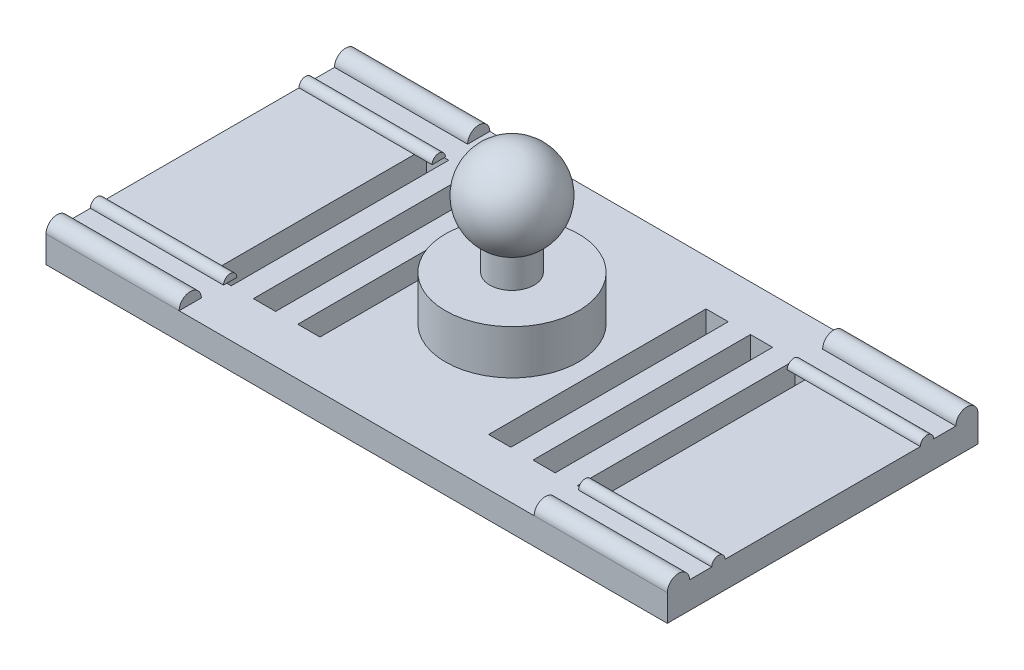
SolidWorks part; units mm, degrees
ref_plane "前视" through (0, 0, 0) normal (0, 0, 1) x (1, 0, 0)
ref_plane "上视" through (0, 0, 0) normal (0, 1, 0) x (1, 0, 0)
ref_plane "右视" through (0, 0, 0) normal (1, 0, 0) x (0, 0, -1)
sketch "草图1" plane through (0, 0, 0) normal (0, 1, 0) x (1, 0, 0)
  line L0 (-66.27, -34.8522) -> (73.73, -34.8522)
  line L2 (-66.27, 35.1478) -> (-66.27, -34.8522)
  line L4 (73.73, 35.1478) -> (73.73, -34.8522)
  line L5 (-66.27, 35.1478) -> (73.73, 35.1478)
extrude "凸台-拉伸1" add sketch "草图1" along normal blind 6
sketch "草图2" plane through (0, 6, 0) normal (0, 1, 0) x (1, 0, 0)
  circle A1 centre (3.73, 0.1478) radius 15
extrude "凸台-拉伸2" add sketch "草图2" along normal blind 10
sketch "草图5" plane through (0, 16, 0) normal (0, 1, 0) x (1, 0, 0)
  circle A0 centre (3.73, 0.1478) radius 5
extrude "凸台-拉伸4" add sketch "草图5" along normal blind 15
sketch "草图6" plane through (0, 31, 0) normal (0, 1, 0) x (1, 0, 0)
  line L0 (3.73, 10.0478) -> (3.73, -9.7522)
  arc A0 (3.73, -9.7522) -> (3.73, 10.0478) centre (3.73, 0.1478) ccw
revolve "旋转2" add sketch "草图6" angle 360 about L0
sketch "草图7" plane through (0, 0, 0) normal (0, -1, 0) x (1, 0, 0)
  line L0 (27.73, -24.8809) -> (22.73, -24.8809)
  line L1 (-35.27, -24.8809) -> (-40.27, -24.8809)
  line L2 (-35.27, -24.8809) -> (-35.27, 24.1191)
  line L3 (27.73, -24.8809) -> (27.73, 24.1191)
  line L4 (37.73, -24.8809) -> (32.73, -24.8809)
  line L5 (37.73, -24.8809) -> (37.73, 24.1191)
  line L6 (37.73, 24.1191) -> (32.73, 24.1191)
  line L7 (32.73, -24.8809) -> (32.73, 24.1191)
  line L8 (27.73, 24.1191) -> (22.73, 24.1191)
  line L9 (22.73, -24.8809) -> (22.73, 24.1191)
  line L10 (-35.27, 24.1191) -> (-40.27, 24.1191)
  line L11 (-40.27, -24.8809) -> (-40.27, 24.1191)
  line L12 (47.73, -24.8809) -> (42.73, -24.8809)
  line L13 (42.73, -24.8809) -> (42.73, 24.1191)
  line L14 (47.73, 24.1191) -> (42.73, 24.1191)
  line L15 (47.73, -24.8809) -> (47.73, 24.1191)
  line L26 (-25.27, -24.8809) -> (-30.27, -24.8809)
  line L27 (-25.27, -24.8809) -> (-25.27, 24.1191)
  line L28 (-15.27, -24.8809) -> (-20.27, -24.8809)
  line L29 (-15.27, -24.8809) -> (-15.27, 24.1191)
  line L30 (-15.27, 24.1191) -> (-20.27, 24.1191)
  line L31 (-20.27, -24.8809) -> (-20.27, 24.1191)
  line L32 (-25.27, 24.1191) -> (-30.27, 24.1191)
  line L33 (-30.27, -24.8809) -> (-30.27, 24.1191)
extrude "切除-拉伸1" cut sketch "草图7" against normal blind 6
sketch "草图9" plane through (-66.27, 0, 0) normal (-1, 0, 0) x (0, 0, 1)
  line L0 (29.8522, 6) -> (34.8522, 6)
  line L1 (-35.1478, 6) -> (-30.1478, 6)
  line L2 (21.8522, 6) -> (24.8522, 6)
  line L3 (-25.1478, 6) -> (-22.1478, 6)
  arc A0 (-30.1478, 6) -> (-35.1478, 6) centre (-32.6478, 6) ccw
  arc A1 (34.8522, 6) -> (29.8522, 6) centre (32.3522, 6) ccw
  arc A3 (24.8522, 6) -> (21.8522, 6) centre (23.3522, 6) ccw
  arc A4 (-22.1478, 6) -> (-25.1478, 6) centre (-23.6478, 6) ccw
extrude "凸台-拉伸5" add sketch "草图9" against normal blind 30
sketch "草图11" plane through (73.73, 0, 0) normal (1, 0, 0) x (0, 0, -1)
  line L0 (30.1478, 6) -> (35.1478, 6)
  line L1 (-34.8522, 6) -> (-29.8522, 6)
  line L2 (22.1478, 6) -> (25.1478, 6)
  line L3 (-24.8522, 6) -> (-21.8522, 6)
  arc A0 (-29.8522, 6) -> (-34.8522, 6) centre (-32.3522, 6) ccw
  arc A1 (35.1478, 6) -> (30.1478, 6) centre (32.6478, 6) ccw
  arc A2 (25.1478, 6) -> (22.1478, 6) centre (23.6478, 6) ccw
  arc A3 (-21.8522, 6) -> (-24.8522, 6) centre (-23.3522, 6) ccw
extrude "凸台-拉伸6" add sketch "草图11" against normal blind 30
